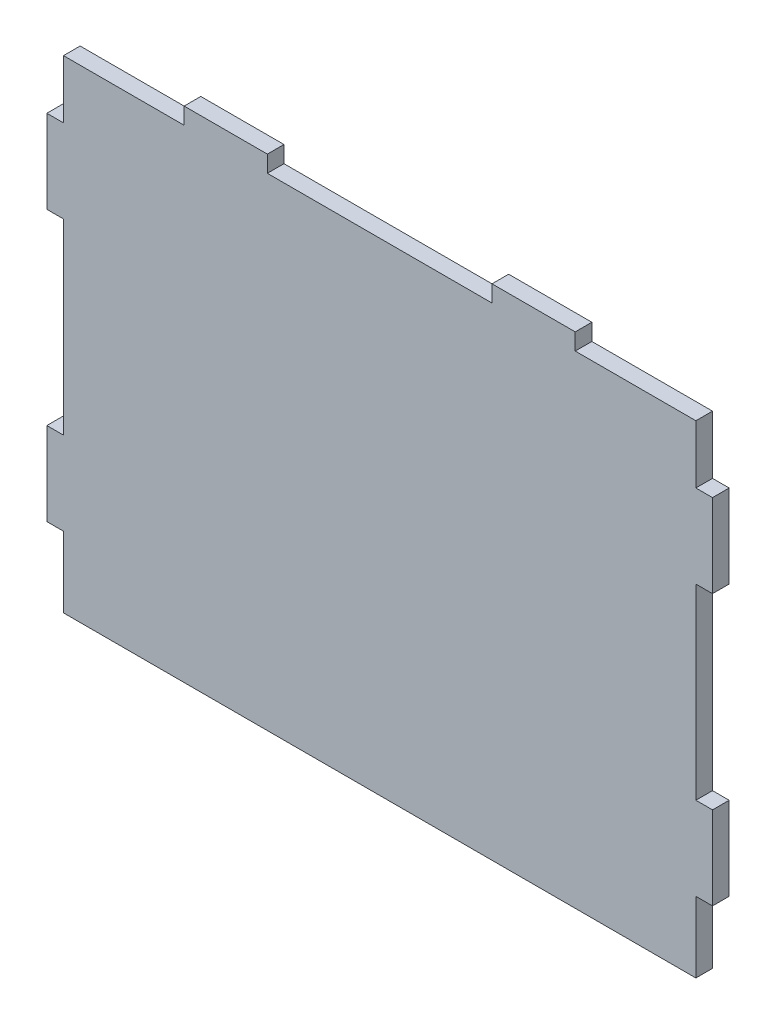
SolidWorks part; units mm, degrees
ref_plane "Front Plane" through (0, 0, 0) normal (0, 0, 1) x (1, 0, 0)
ref_plane "Top Plane" through (0, 0, 0) normal (0, 1, 0) x (1, 0, 0)
ref_plane "Right Plane" through (0, 0, 0) normal (1, 0, 0) x (0, 0, -1)
sketch "Sketch1" plane through (0, 0, 0) normal (0, 0, 1) x (1, 0, 0)
  line L0 (96.52, -29.21) -> (96.52, -3.81) construction
  line L1 (-96.52, 96.52) -> (96.52, 96.52)
  line L2 (-96.52, 96.52) -> (-96.52, -50.8)
  line L3 (-96.52, -50.8) -> (96.52, -50.8)
  line L4 (96.52, 96.52) -> (96.52, -50.8)
  line L5 (101.6, 101.6) -> (96.52, 101.6) construction
  line L6 (59.69, 101.6) -> (34.29, 101.6) construction
  line L8 (-59.69, 101.6) -> (-34.29, 101.6)
  line L9 (-59.69, 101.6) -> (-59.69, 96.52)
  line L10 (-59.69, 96.52) -> (-34.29, 96.52)
  line L11 (-34.29, 101.6) -> (-34.29, 96.52)
  line L12 (34.29, 101.6) -> (59.69, 101.6)
  line L13 (34.29, 101.6) -> (34.29, 96.52)
  line L14 (34.29, 96.52) -> (59.69, 96.52)
  line L15 (59.69, 101.6) -> (59.69, 96.52)
  line L16 (101.6, 78.74) -> (96.52, 78.74)
  line L17 (101.6, 78.74) -> (101.6, 53.34)
  line L18 (101.6, 53.34) -> (96.52, 53.34)
  line L19 (96.52, 78.74) -> (96.52, 53.34)
  line L20 (101.6, -3.81) -> (96.52, -3.81)
  line L21 (101.6, -3.81) -> (101.6, -29.21)
  line L22 (101.6, -29.21) -> (96.52, -29.21)
  line L23 (96.52, -3.81) -> (96.52, -29.21)
  line L24 (-101.6, -29.21) -> (-96.52, -29.21)
  line L25 (-101.6, -29.21) -> (-101.6, -3.81)
  line L26 (-101.6, -3.81) -> (-96.52, -3.81)
  line L27 (-96.52, -29.21) -> (-96.52, -3.81)
  line L28 (-101.6, 53.34) -> (-96.52, 53.34)
  line L29 (-101.6, 53.34) -> (-101.6, 78.74)
  line L30 (-101.6, 78.74) -> (-96.52, 78.74)
  line L31 (-96.52, 53.34) -> (-96.52, 78.74)
  line L32 (-96.52, 53.34) -> (-96.52, 78.74) construction
  line L33 (-59.69, 101.6) -> (-96.52, 101.6) construction
  line L34 (-101.6, -29.21) -> (-101.6, -50.8) construction
  line L35 (59.69, 96.52) -> (34.29, 96.52) construction
  line L36 (-101.6, 78.74) -> (-96.52, 78.74) construction
  point P8 (99.06, 101.6)
  point P13 (-99.06, -29.21)
  dimension "D1" = 193.04
  dimension "D2" = 147.32
  dimension "D3" = 22.86
  dimension "D4" = 25.4
  dimension "D5" = 5.08
  dimension "D6" = 5.08
  dimension "D7" = 5.08
  dimension "D8" = 21.59
  dimension "D9" = 5.08
  dimension "D10" = 36.83
  dimension "D11" = 36.83
  dimension "D12" = 21.59
  dimension "D13" = 5.08
  dimension "D14" = 5.08
  dimension "D15" = 5.08
  dimension "D16" = 5.08
  dimension "D17" = 5.08
  dimension "D18" = 5.08
  dimension "D19" = 5.08
extrude "Boss-Extrude2" add sketch "Sketch1" along normal blind 5.08 contours L4 L1 L2 L3 | L11 L8 L9 L1 | L15 L12 L13 L1 | L18 L17 L16 L4 | L22 L21 L20 L4 | L26 L25 L24 L2 | L30 L29 L28 L2
